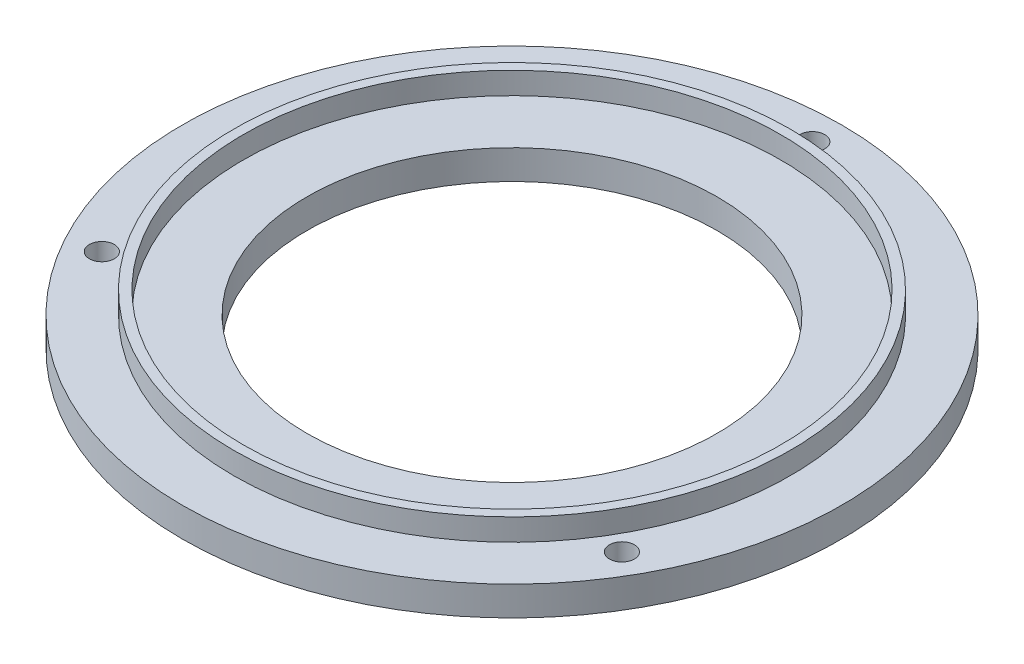
SolidWorks part; units mm, degrees
material "PETG (Black)"
ref_plane "Front Plane" through (0, 0, 0) normal (0, 0, 1) x (1, 0, 0)
ref_plane "Top Plane" through (0, 0, 0) normal (0, 1, 0) x (1, 0, 0)
ref_plane "Right Plane" through (0, 0, 0) normal (1, 0, 0) x (0, 0, -1)
sketch "Sketch1" plane through (0, 0, 0) normal (0, 1, 0) x (1, 0, 0)
  circle A0 centre (0, 0) radius 45
  circle A1 centre (0, 0) radius 28
  dimension "D1" = 90
  dimension "D2" = 56
extrude "Collar_Annulus_OD90_ID56_T4" add sketch "Sketch1" along normal blind 4
sketch "Sketch2" plane through (0, 4, 0) normal (0, 1, 0) x (1, 0, 0)
  circle A0 centre (0, 0) radius 38
  circle A1 centre (0, 0) radius 36.7
  dimension "D1" = 76
  dimension "D2" = 73.4
extrude "Retaining_Rim_OD76_ID73.4_H3" add sketch "Sketch2" along normal blind 3
hole_wizard "Mounting_Holes_3xØ3.4_PCD82" positions "Sketch3" profile "Sketch4" hole size "Ø3.4" standard "ISO" end condition through all
sketch "Sketch3" plane through (0, 4, 0) normal (0, 1, 0) x (1, 0, 0)
  circle A0 centre (0, 0) radius 41
  point P5 (0, 41)
  point P15 (35.507, -20.5)
  point P16 (-35.507, -20.5)
  dimension "D1" = 82
  dimension "D2" = 41
  dimension "D3" = 41
  dimension "D4" = 3
sketch "Sketch4" plane through (-35.507, 4, 20.5) normal (1, 0, 0) x (0, 0, 1)
  line L0 (0, 0) -> (0, 4)
  line L1 (0, 4) -> (1.7, 4)
  line L2 (1.7, 4) -> (1.7, 0)
  line L5 (1.7, 0) -> (0, 0)
  line L11 (0, -6.35) -> (0, 107.95) construction
  dimension "Thru Hole Dia." = 3.4
  dimension "Thru Hole Depth" = 4
